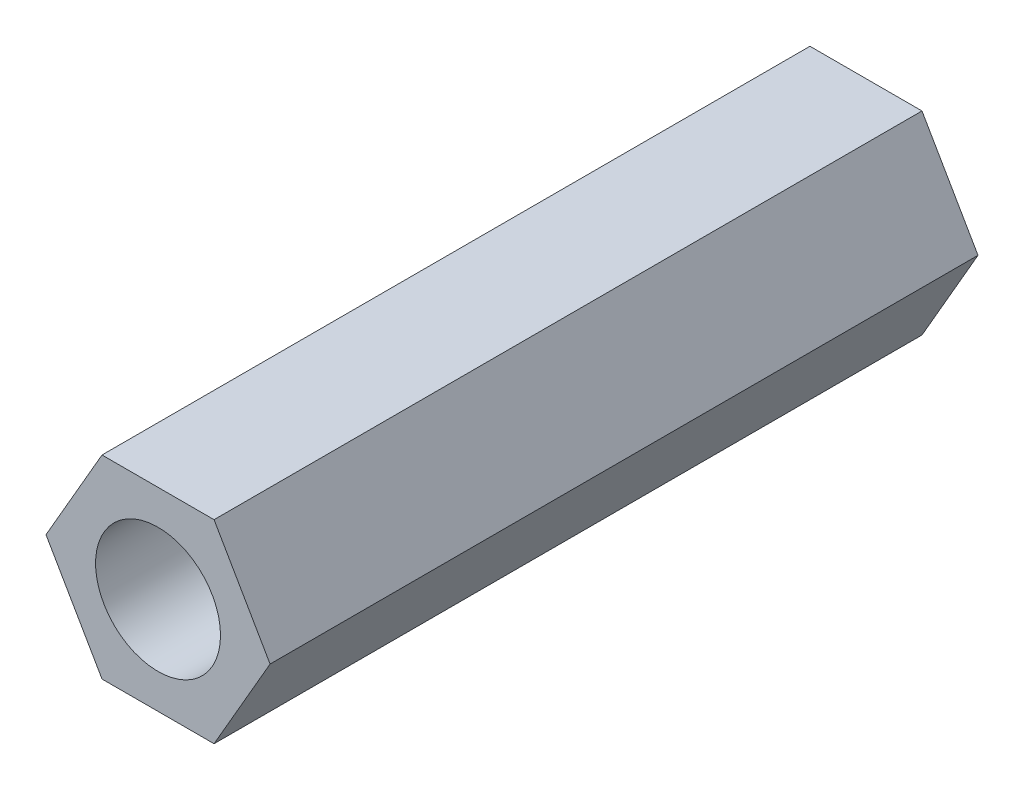
SolidWorks part; units mm, degrees
material "Brass"
ref_plane "Front Plane" through (0, 0, 0) normal (0, 0, 1) x (1, 0, 0)
ref_plane "Top Plane" through (0, 0, 0) normal (0, 1, 0) x (1, 0, 0)
ref_plane "Right Plane" through (0, 0, 0) normal (1, 0, 0) x (0, 0, -1)
sketch "Sketch1" plane through (0, 0, 0) normal (0, 0, 1) x (1, 0, 0)
  line L1 (2.6905, 0) -> (1.3452, 2.33)
  line L2 (1.3452, 2.33) -> (-1.3452, 2.33)
  line L3 (-1.3452, 2.33) -> (-2.6905, 0)
  line L4 (-2.6905, 0) -> (-1.3452, -2.33)
  line L5 (-1.3452, -2.33) -> (1.3452, -2.33)
  line L6 (1.3452, -2.33) -> (2.6905, 0)
  circle A0 centre (0, 0) radius 2.33 construction
  dimension "D1" = 4.66
extrude "Boss-Extrude1" add sketch "Sketch1" along normal blind 17
sketch "Sketch2" plane through (0, 0, 17) normal (0, 0, 1) x (1, 0, 0)
  circle A0 centre (0, 0) radius 1.5
  dimension "D1" = 3
extrude "Cut-Extrude1" cut sketch "Sketch2" against normal blind 17
